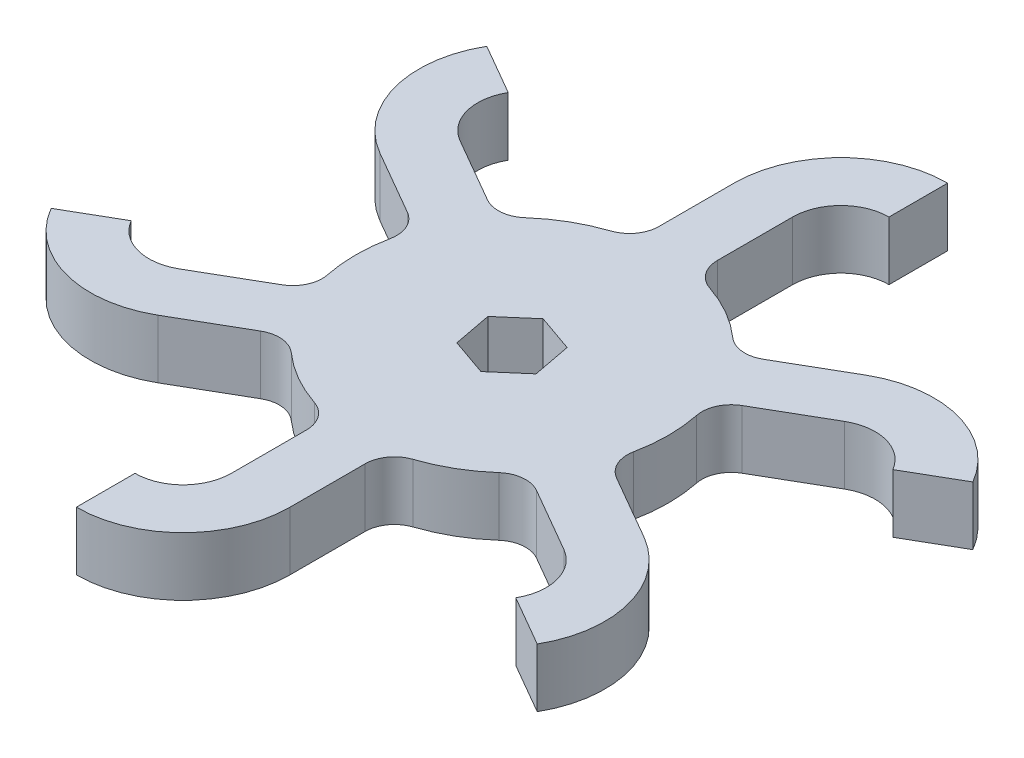
SolidWorks part; units mm, degrees
ref_plane "前视基准面" through (0, 0, 0) normal (0, 0, 1) x (1, 0, 0)
ref_plane "上视基准面" through (0, 0, 0) normal (0, 1, 0) x (1, 0, 0)
ref_plane "右视基准面" through (0, 0, 0) normal (1, 0, 0) x (0, 0, -1)
sketch "草图1" plane through (0, 0, 0) normal (0, 1, 0) x (1, 0, 0)
  line L0 (0, 0) -> (0, 37.5) construction
  line L1 (-3, 15.7162) -> (-3, 25.7162)
  line L2 (3, 15.7162) -> (3, 25.7162)
  line L3 (7.9313, 30.6517) -> (7.9313, 36.6517)
  line L5 (-0.75, 3.9291) -> (-3, 15.7162)
  line L6 (3.0277, 2.614) -> (12.1107, 10.4562)
  line L7 (-0.75, 3.9291) -> (3.0277, 2.614)
  circle A0 centre (0, 0) radius 37.5 construction
  arc A1 (12.1107, 10.4562) -> (3, 15.7162) centre (0, 0) ccw construction
  arc A2 (-3, 25.7162) -> (7.9313, 36.6517) centre (7.9354, 25.7162) cw
  arc A4 (3, 25.7162) -> (7.9313, 30.6517) centre (7.9354, 25.7162) cw
  arc A5 (12.1107, 10.4562) -> (3, 15.7162) centre (0, 0) ccw
  dimension "D1" = 75
  dimension "D2" = 16
  dimension "D3" = 6
  dimension "D4" = 10
  dimension "D5" = 6
  dimension "D6" = 60
  dimension "D7" = 10
  dimension "D8" = 4
  dimension "D9" = 60
  dimension "D10" = 12
  dimension "D11" = 12
extrude "凸台-拉伸1" add sketch "草图1" along normal blind 6
pattern_circular "阵列(圆周)1" count 6 over 360 about axis through (0, 0, 0) along (0, 1, 0) of "凸台-拉伸1"
fillet "圆角1" radius 3 12 edges at (15.1107, 3, -5.26) (12.1107, 3, -10.4562) (3, 3, -15.7162) (-3, 3, -15.7162) (-12.1107, 3, -10.4562) (-15.1107, 3, -5.26) (-15.1107, 3, 5.26) (-12.1107, 3, 10.4562) (-3, 3, 15.7162) (3, 3, 15.7162) (12.1107, 3, 10.4562) (15.1107, 3, 5.26)
